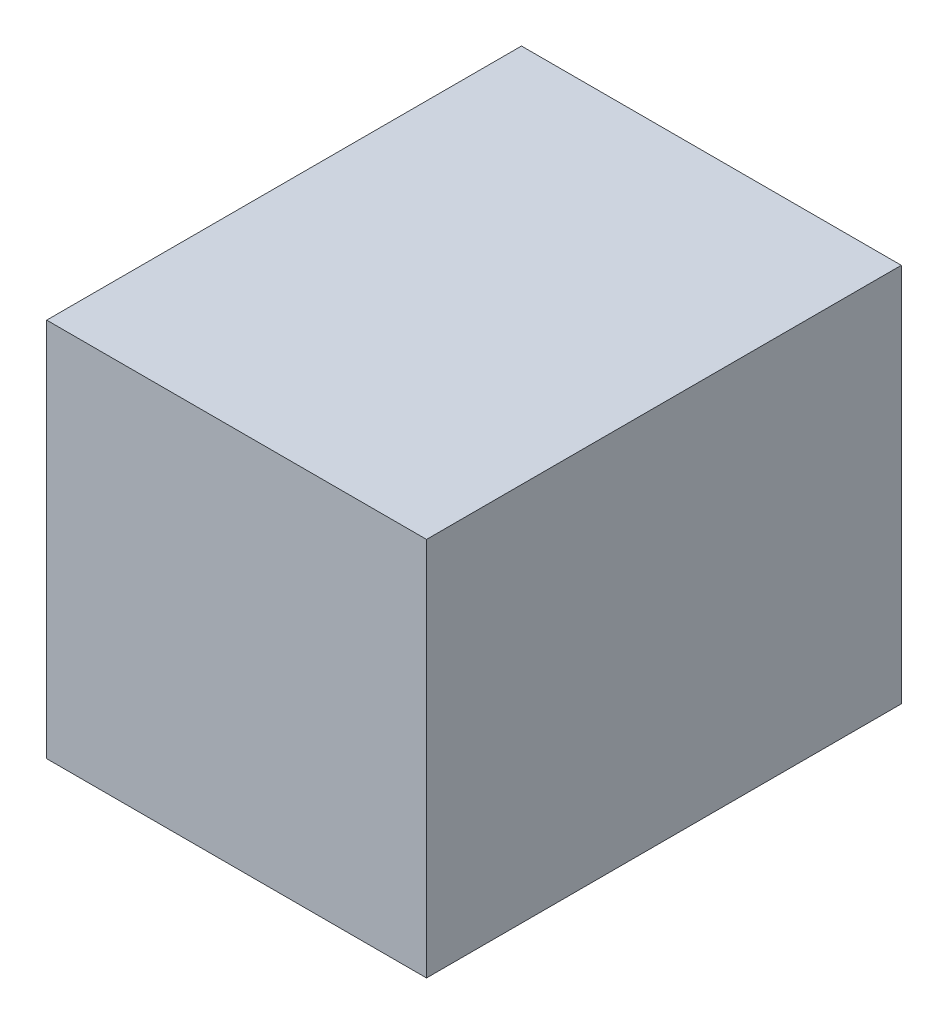
SolidWorks part; units mm, degrees
ref_plane "前基準面" through (0, 0, 0) normal (0, 0, 1) x (1, 0, 0)
ref_plane "上基準面" through (0, 0, 0) normal (0, 1, 0) x (1, 0, 0)
ref_plane "右基準面" through (0, 0, 0) normal (1, 0, 0) x (0, 0, -1)
sketch "草圖1" plane through (0, 0, 0) normal (0, 1, 0) x (1, 0, 0)
  line L1 (-80, 100) -> (80, 100)
  line L2 (-80, 100) -> (-80, -100)
  line L3 (-80, -100) -> (80, -100)
  line L4 (80, 100) -> (80, -100)
  line L5 (-80, 100) -> (80, -100) construction
  line L6 (-80, -100) -> (80, 100) construction
  point P0 (0, 0)
  point P5 (0, 0)
  dimension "D1" = 200
  dimension "D2" = 160
extrude "車子範圍" add sketch "草圖1" along normal blind 160
sketch "輪子+馬達" plane through (0, 0, 0) normal (0, 1, 0) x (1, 0, 0)
  line L0 (24.5, 83.2) -> (61.3, 83.2)
  line L1 (53.4, 100) -> (80, 100)
  line L2 (53.4, 100) -> (53.4, 34)
  line L3 (53.4, 34) -> (80, 34)
  line L4 (80, 100) -> (80, 34)
  line L5 (53.4, 100) -> (80, 34) construction
  line L6 (53.4, 34) -> (80, 100) construction
  line L7 (24.5, 83.2) -> (24.5, 14)
  line L8 (24.5, 14) -> (61.3, 14)
  line L9 (61.3, 83.2) -> (61.3, 14)
  line L10 (24.5, 83.2) -> (61.3, 14) construction
  line L11 (24.5, 14) -> (61.3, 83.2) construction
  line L12 (0, 0) -> (0, 48.5992) construction
  line L13 (-24.5, 14) -> (-61.3, 83.2) construction
  line L14 (-24.5, 83.2) -> (-61.3, 14) construction
  line L15 (-53.4, 34) -> (-80, 100) construction
  line L16 (-53.4, 100) -> (-80, 34) construction
  line L17 (-61.3, 83.2) -> (-61.3, 14)
  line L18 (-24.5, 14) -> (-61.3, 14)
  line L19 (-24.5, 83.2) -> (-24.5, 14)
  line L20 (-80, 100) -> (-80, 34)
  line L21 (-53.4, 34) -> (-80, 34)
  line L22 (-53.4, 100) -> (-53.4, 34)
  line L23 (-53.4, 100) -> (-80, 100)
  line L24 (-24.5, 83.2) -> (-61.3, 83.2)
  line L25 (-80, 100) -> (-80, -100) construction
  line L26 (0, 0) -> (40.3631, 0) construction
  line L27 (-80, 100) -> (80, 100) construction
  point P0 (66.7, 67)
  point P5 (42.9, 48.6)
  point P10 (61.3, 67)
  point P22 (-61.3, 67)
  point P23 (-42.9, 48.6)
  point P24 (-66.7, 67)
  point P25 (0, 0)
  point P26 (-39.6615, 44.6621)
  dimension "D1" = 66
  dimension "D2" = 26.6
  dimension "D3" = 36.8
  dimension "D4" = 69.2
  dimension "D5" = 16.2
  dimension "D6" = 7.9
  dimension "D7" = 49
  dimension "D8" = 85.8
ref_plane "平面1" through (0, 0, 0) normal (-1, 0, 0) x (0, 0, 1)
sketch "五路感測器" plane through (0, 0, 0) normal (0, 1, 0) x (1, 0, 0)
  line L0 (0, -89.85) -> (0, -100) construction
  line L1 (48.25, -100) -> (-48.25, -100)
  line L2 (48.25, -100) -> (48.25, -79.7)
  line L3 (48.25, -79.7) -> (-48.25, -79.7)
  line L4 (-48.25, -100) -> (-48.25, -79.7)
  line L5 (48.25, -100) -> (-48.25, -79.7) construction
  line L6 (48.25, -79.7) -> (-48.25, -100) construction
  line L7 (0, 88) -> (0, -88) construction
  line L8 (-80, -100) -> (80, -100) construction
  circle A0 centre (0, -96.85) radius 1.5
  circle A1 centre (-21.9966, -97.234) radius 1.5
  circle A2 centre (-43.9933, -97.6179) radius 1.5
  circle A3 centre (21.9966, -96.466) radius 1.5
  circle A4 centre (43.9933, -96.0821) radius 1.5
  point P0 (0, -89.85)
  point P8 (0, 0)
  point P16 (0, 0)
  point P17 (40.1562, -136.5157)
  point P18 (4.6762, -82.1232)
  point P19 (0.6793, -92.2732)
  point P20 (-6.1845, -80.0813)
  point P23 (0, -84.1603)
  dimension "D3" = 3
  dimension "D1" = 96.5
  dimension "D2" = 20.3
  dimension "D6" = 7
  dimension "D4" = 3
  dimension "D5" = 3
sketch "前輪" plane through (0, 0, 0) normal (0, 1, 0) x (1, 0, 0)
  line L5 (0, 88) -> (0, -88) construction
  line L6 (-7.3586, -55.234) -> (7.3586, -55.234)
  line L8 (-7.3586, -55.234) -> (-7.3586, -85.441)
  line L10 (-7.3586, -85.441) -> (7.3586, -85.441)
  line L11 (7.3586, -55.234) -> (7.3586, -85.441)
  line L12 (-7.3586, -55.234) -> (7.3586, -85.441) construction
  line L13 (-7.3586, -85.441) -> (7.3586, -55.234) construction
  point P0 (0, -70.3375)
  point P12 (-42.9, 48.6)
